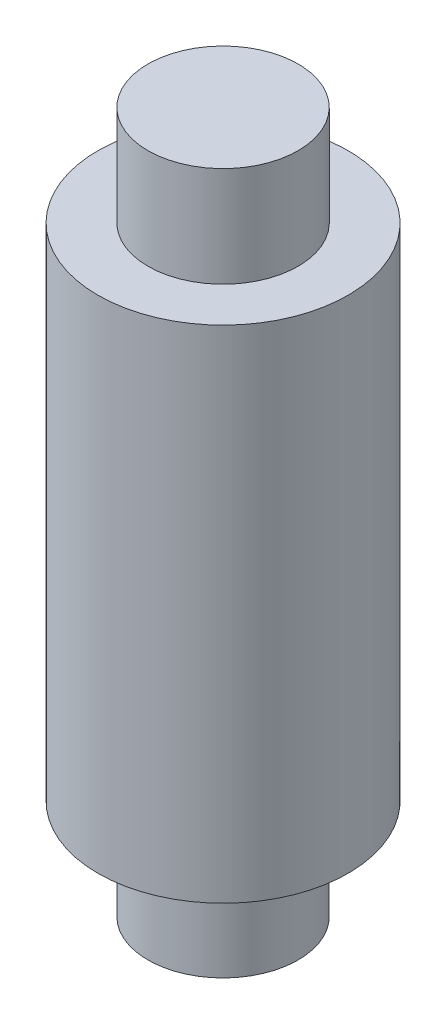
SolidWorks part; units mm, degrees
ref_plane "Спереди" through (0, 0, 0) normal (0, 0, 1) x (1, 0, 0)
ref_plane "Сверху" through (0, 0, 0) normal (0, 1, 0) x (1, 0, 0)
ref_plane "Справа" through (0, 0, 0) normal (1, 0, 0) x (0, 0, -1)
sketch "Эскиз1" plane through (0, 0, 0) normal (0, 1, 0) x (1, 0, 0)
  circle A0 centre (0, 0) radius 2.5
  dimension "D1" = 5
extrude "Бобышка-Вытянуть1" add sketch "Эскиз1" along normal blind 10
sketch "Эскиз2" plane through (0, 10, 0) normal (0, 1, 0) x (1, 0, 0)
  circle A0 centre (0, 0) radius 1.5
  dimension "D1" = 3
extrude "Бобышка-Вытянуть2" add sketch "Эскиз2" along normal blind 2
sketch "Эскиз4" plane through (0, 0, 0) normal (0, -1, 0) x (1, 0, 0)
  circle A0 centre (0, 0) radius 1.5
  circle A1 centre (0, 0) radius 1.5 construction
extrude "Бобышка-Вытянуть3" add sketch "Эскиз4" along normal blind 2
